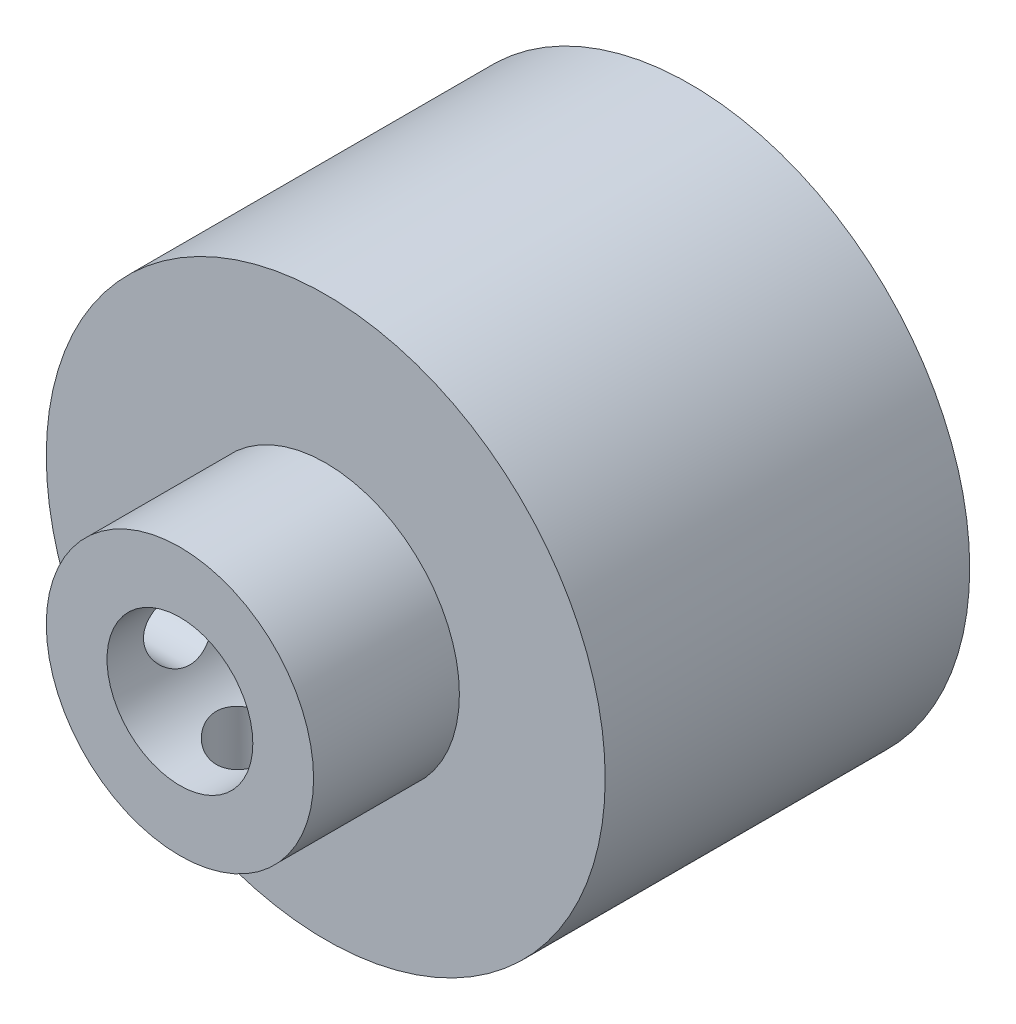
SolidWorks part; units mm, degrees
ref_plane "Front Plane" through (0, 0, 0) normal (0, 0, 1) x (1, 0, 0)
ref_plane "Top Plane" through (0, 0, 0) normal (0, 1, 0) x (1, 0, 0)
ref_plane "Right Plane" through (0, 0, 0) normal (1, 0, 0) x (0, 0, -1)
sketch "Sketch1" plane through (0, 0, 0) normal (0, 0, 1) x (1, 0, 0)
  circle A0 centre (0, 0) radius 11.5
  dimension "D1" = 23
extrude "Boss-Extrude1" add sketch "Sketch1" along normal blind 15
sketch "Sketch2" plane through (0, 0, 15) normal (0, 0, 1) x (1, 0, 0)
  circle A0 centre (0, 0) radius 5.5
  dimension "D1" = 11
extrude "Boss-Extrude2" add sketch "Sketch2" along normal blind 6
sketch "Sketch3" plane through (0, 0, 21) normal (0, 0, 1) x (1, 0, 0)
  circle A0 centre (0, 0) radius 3
  dimension "D1" = 6
extrude "Cut-Extrude1" cut sketch "Sketch3" against normal through all contours A0
sketch "Sketch4" plane through (0, 0, 0) normal (0, 1, 0) x (1, 0, 0)
  line L0 (5.5, -21) -> (5.5, -15) construction
  circle A0 centre (0, -18) radius 1.5
  point P2 (0, 0)
  point P4 (5.5, -18)
  dimension "D1" = 3
extrude "Cut-Extrude2" cut sketch "Sketch4" against normal through all
sketch "Sketch5" plane through (0, 0, 0) normal (1, 0, 0) x (0, 0, -1)
  line L0 (-15, 5.5) -> (-21, 5.5) construction
  circle A0 centre (-18, 0) radius 1.5
  point P2 (0, 0)
  point P4 (-18, 5.5)
  dimension "D1" = 3
extrude "Cut-Extrude3" cut sketch "Sketch5" against normal through all
